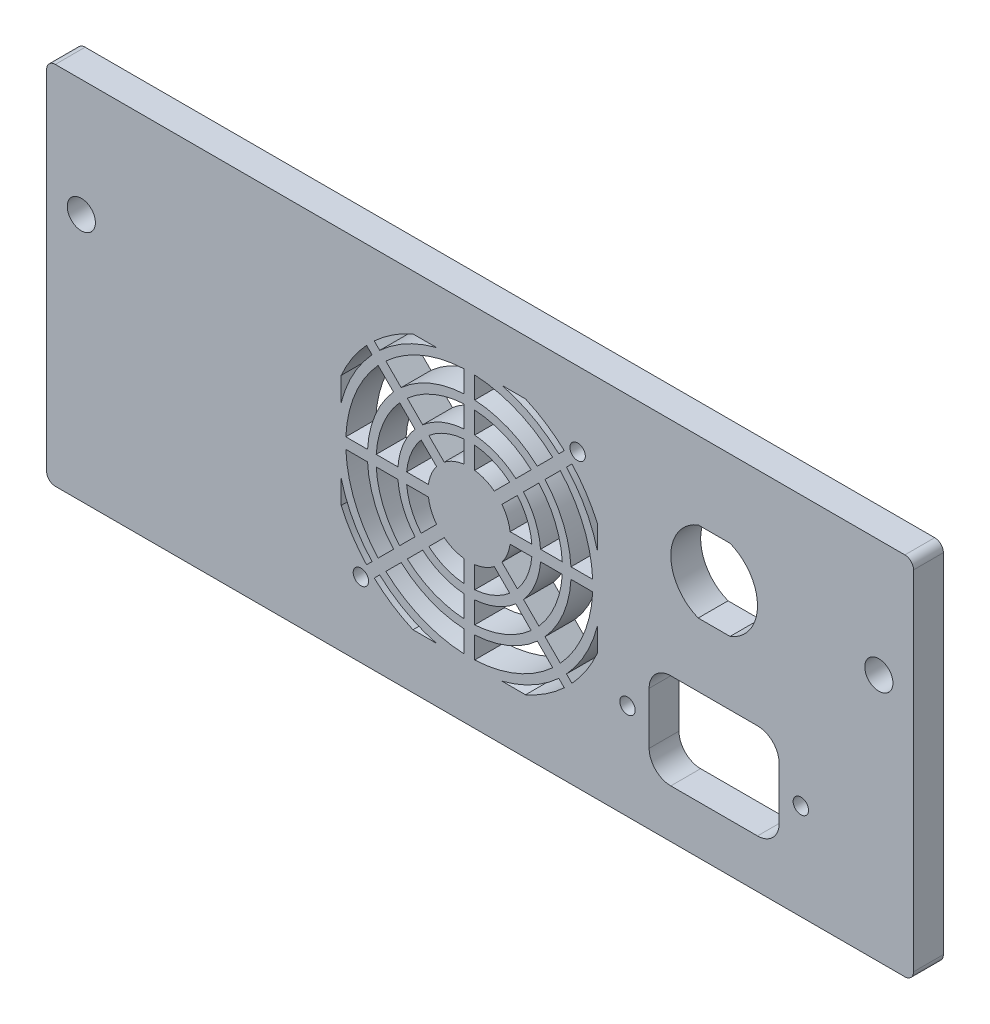
SolidWorks part; units mm, degrees
ref_plane "Front Plane" through (0, 0, 0) normal (0, 0, 1) x (1, 0, 0)
ref_plane "Top Plane" through (0, 0, 0) normal (0, 1, 0) x (1, 0, 0)
ref_plane "Right Plane" through (0, 0, 0) normal (1, 0, 0) x (0, 0, -1)
sketch "Sketch1" plane through (0, 0, 0) normal (0, 0, 1) x (1, 0, 0)
  line L1 (100, -42.15) -> (-100, -42.15)
  line L2 (100, -42.15) -> (100, 42.15)
  line L3 (100, 42.15) -> (-100, 42.15)
  line L4 (-100, -42.15) -> (-100, 42.15)
  line L5 (100, -42.15) -> (-100, 42.15) construction
  line L6 (100, 42.15) -> (-100, -42.15) construction
  point P0 (0, 0)
  dimension "D1" = 200
  dimension "D2" = 84.3
extrude "Boss-Extrude1" add sketch "Sketch1" along normal blind 6.88
sketch "Sketch2" plane through (0, 0, 6.88) normal (0, 0, 1) x (1, 0, 0)
  line L0 (100, 42.15) -> (-100, 42.15) construction
  line L1 (92, 15.15) -> (-92, 15.15) construction
  circle A0 centre (-92, 15.15) radius 3.25
  circle A1 centre (92, 15.15) radius 3.25
  point P10 (0, 15.15)
  dimension "D1" = 6.5
  dimension "D2" = 92
  dimension "D3" = 27
extrude "Cut-Extrude1" cut sketch "Sketch2" against normal blind 6.88
fillet "Fillet1" radius 2 4 edges at (100, 42.15, 3.44) (100, -42.15, 3.44) (-100, -42.15, 3.44) (-100, 42.15, 3.44)
sketch "Sketch3" plane through (0, 0, 6.88) normal (0, 0, 1) x (1, 0, 0)
  line L0 (74, -20) -> (69, -20) construction
  line L1 (39, -9) -> (69, -9)
  line L2 (39, -9) -> (39, -31)
  line L3 (39, -31) -> (69, -31)
  line L4 (69, -9) -> (69, -31)
  line L5 (39, -9) -> (69, -31) construction
  line L6 (39, -31) -> (69, -9) construction
  line L7 (39, -20) -> (34, -20) construction
  line L8 (50.3244, 24.3) -> (57.6756, 24.3)
  line L9 (57.6756, 5.7) -> (50.3244, 5.7)
  line L10 (54, 24.3) -> (54, 15) construction
  line L11 (54, 15) -> (54, 5.7) construction
  circle A2 centre (34, -20) radius 1.775
  circle A3 centre (74, -20) radius 1.775
  arc A4 (57.6756, 5.7) -> (57.6756, 24.3) centre (54, 15) ccw
  arc A5 (50.3244, 24.3) -> (50.3244, 5.7) centre (54, 15) ccw
  point P0 (54, -20)
  dimension "D3" = 3.55
  dimension "D7" = 20
  dimension "D1" = 22
  dimension "D2" = 30
  dimension "D4" = 5
  dimension "D5" = 54
  dimension "D6" = 20
  dimension "D8" = 18.6
  dimension "D9" = 35
extrude "Cut-Extrude2" cut sketch "Sketch3" against normal up to vertex (6.88 mm away) up to point (0, 0, 0)
fillet "Fillet2" radius 5 4 edges at (69, -31, 3.44) (39, -31, 3.44) (39, -9, 3.44) (69, -9, 3.44)
sketch "Sketch4" plane through (0, 0, 6.88) normal (0, 0, 1) x (1, 0, 0)
  line L0 (-32.05, 12.9909) -> (-32.05, -12.9909)
  line L1 (-15.4909, -29.55) -> (10.4909, -29.55)
  line L2 (27.05, -12.9909) -> (27.05, 12.9909)
  line L3 (10.4909, 29.55) -> (-15.4909, 29.55)
  line L5 (22.5, -25) -> (-27.5, -25) construction
  line L6 (22.5, -25) -> (22.5, 25) construction
  line L7 (22.5, 25) -> (-27.5, 25) construction
  line L8 (-27.5, -25) -> (-27.5, 25) construction
  line L9 (22.5, -25) -> (-27.5, 25) construction
  line L10 (22.5, 25) -> (-27.5, -25) construction
  circle A4 centre (22.5, 25) radius 1.775
  circle A5 centre (-27.5, 25) radius 1.775 construction
  circle A6 centre (-27.5, -25) radius 1.775
  circle A7 centre (22.5, -25) radius 1.775 construction
  arc A10 (27.05, 12.9909) -> (10.4909, 29.55) centre (-2.5, 0) ccw
  arc A11 (-15.4909, 29.55) -> (-32.05, 12.9909) centre (-2.5, 0) ccw
  arc A14 (-32.05, -12.9909) -> (-15.4909, -29.55) centre (-2.5, 0) ccw
  arc A15 (10.4909, -29.55) -> (27.05, -12.9909) centre (-2.5, 0) ccw
  circle A17 centre (-2.5, 0) radius 7.5
  circle A19 centre (-2.5, 0) radius 9.5
  circle A20 centre (-2.5, 0) radius 14.5
  circle A21 centre (-2.5, 0) radius 16.5
  circle A22 centre (-2.5, 0) radius 21.5
  circle A23 centre (-2.5, 0) radius 23.5
  circle A24 centre (-2.5, 0) radius 28.5
  arc A25 (-10.053, 29.55) -> (-32.05, 7.553) centre (-2.5, 0) ccw
  arc A27 (-32.05, -7.553) -> (-10.053, -29.55) centre (-2.5, 0) ccw
  arc A28 (5.053, -29.55) -> (27.05, -7.553) centre (-2.5, 0) ccw
  arc A29 (27.05, 7.553) -> (5.053, 29.55) centre (-2.5, 0) ccw
  point P91 (-2.5, 0)
  dimension "D1" = 15
  dimension "D3" = 3.55
  dimension "D2" = 50
extrude "Cut-Extrude3" cut sketch "Sketch4" against normal through all contours A20 A19 | A22 A21 | A24 A23 | A29 L2 A10 L3 | A25 L3 A11 L0 | A27 L0 A14 L1 | A28 L1 A15 L2 | A5 | A4 | A6 | A7
sketch "Sketch7" plane through (0, 0, 6.88) normal (0, 0, 1) x (1, 0, 0)
  line L0 (-2.5, 0) -> (-2.5, 33) construction
  line L1 (-1.25, 0) -> (-1.25, 33)
  line L2 (-3.75, 0) -> (-3.75, 33)
  line L3 (-3.75, 33) -> (-1.25, 33)
  line L4 (-1.25, 0) -> (-3.75, 0)
  dimension "D3" = 33
  dimension "D1" = 1.25
  dimension "D2" = 1.25
extrude "Boss-Extrude2" add sketch "Sketch7" against normal blind 6.88
pattern_circular "CirPattern1" count 8 over 360 about axis through (-2.5, 0, 0) along (0, 0, 1) of "Boss-Extrude2"
sketch "Sketch6" plane through (0, 0, 6.88) normal (0, 0, 1) x (1, 0, 0)
  line L0 (95.6593, -24.1249) -> (86.1331, -7.6249)
  line L1 (85.267, -5.1249) -> (74.0087, -24.6249)
  line L2 (74.8747, -26.1249) -> (97.3914, -26.1249)
  line L3 (98.2574, -24.6249) -> (86.9991, -5.1249)
  line L4 (86.1331, -7.6249) -> (76.6068, -24.1249)
  line L5 (76.6068, -24.1249) -> (95.6593, -24.1249)
  line L8 (85.2625, -12.2742) -> (87.0589, -12.2742)
  line L9 (87.0589, -12.2742) -> (85.8186, -15.8896)
  line L10 (85.8186, -15.8896) -> (87.8625, -14.2347)
  line L11 (87.8625, -14.2347) -> (86.8193, -20.1088)
  line L12 (86.8193, -20.1088) -> (88.0579, -19.106)
  line L13 (88.0579, -19.106) -> (86.3382, -22.1565)
  line L14 (86.3382, -22.1565) -> (84.1346, -19.4349)
  line L15 (84.1346, -19.4349) -> (85.5229, -20.2175)
  line L16 (85.5229, -20.2175) -> (86.1331, -16.8343)
  line L17 (86.1331, -16.8343) -> (83.8541, -17.9655)
  line L18 (83.8541, -17.9655) -> (85.2625, -12.2742)
  circle A0 centre (86.1331, -18.6249) radius 7.5 construction
  arc A1 (98.2574, -24.6249) -> (97.3914, -26.1249) centre (97.3914, -25.1249) cw
  arc A2 (74.8747, -26.1249) -> (74.0087, -24.6249) centre (74.8747, -25.1249) cw
  arc A3 (86.9991, -5.1249) -> (85.267, -5.1249) centre (86.1331, -5.6249) ccw
  arc A4 (86.1331, -7.6249) -> (86.1331, -7.6249) centre (86.1331, -7.6249) ccw
  arc A5 (76.6068, -24.1249) -> (76.6068, -24.1249) centre (76.6068, -24.1249) cw
  arc A6 (95.6593, -24.1249) -> (95.6593, -24.1249) centre (95.6593, -24.1249) cw
  dimension "D1" = 1
  dimension "D3" = 15
  dimension "D2" = 2
extrude "Cut-Extrude4" [suppressed] cut sketch "Sketch6" against normal blind 1 contours L18 L17 L16 L15 L14 L13 L12 L11 L10 L9 L8 | L3 A3 L1 A2 L2 A1 L5 L4 L0
